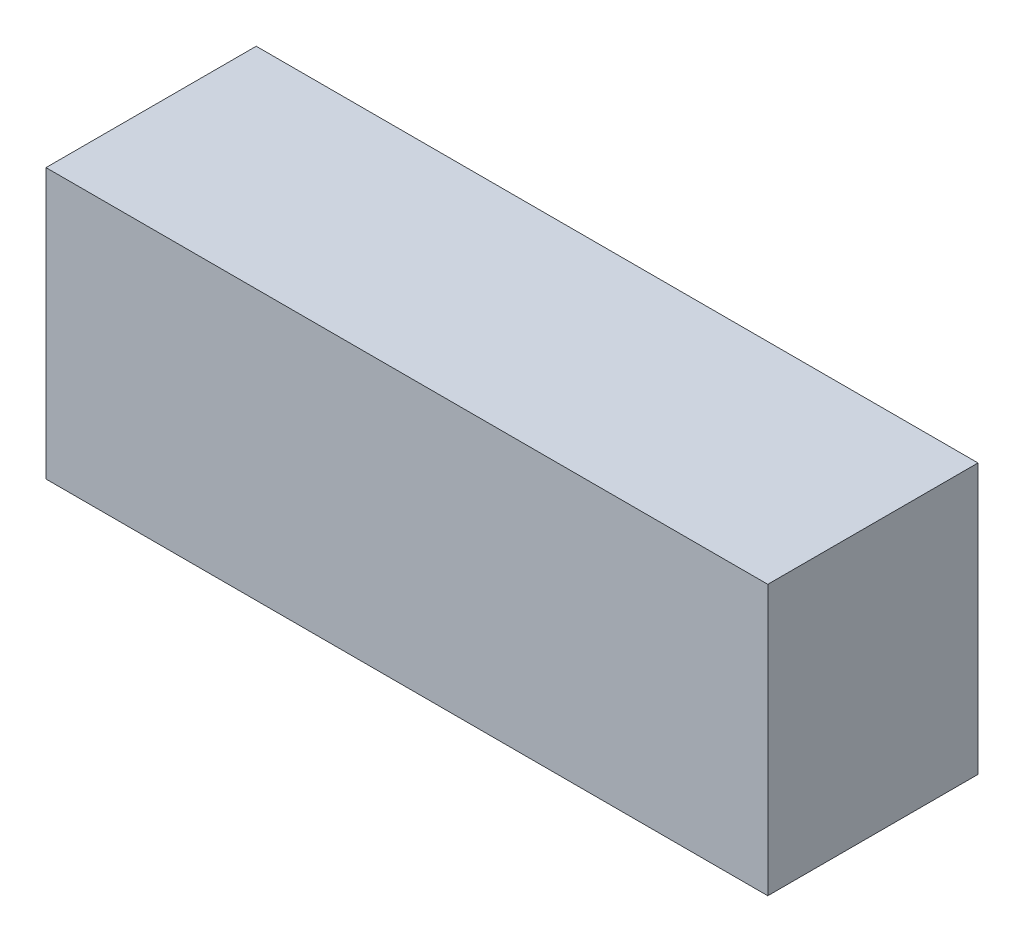
SolidWorks part; units mm, degrees
ref_plane "前视基准面" through (0, 0, 0) normal (0, 0, 1) x (1, 0, 0)
ref_plane "上视基准面" through (0, 0, 0) normal (0, 1, 0) x (1, 0, 0)
ref_plane "右视基准面" through (0, 0, 0) normal (1, 0, 0) x (0, 0, -1)
sketch "草图1" plane through (0, 0, 0) normal (0, 0, 1) x (1, 0, 0)
  line L1 (0, 0) -> (194, 0)
  line L2 (0, 0) -> (0, 72.5)
  line L3 (0, 72.5) -> (194, 72.5)
  line L4 (194, 0) -> (194, 72.5)
  dimension "D1" = 194
  dimension "D2" = 72.5
extrude "凸台-拉伸1" add sketch "草图1" along normal blind 56.5
